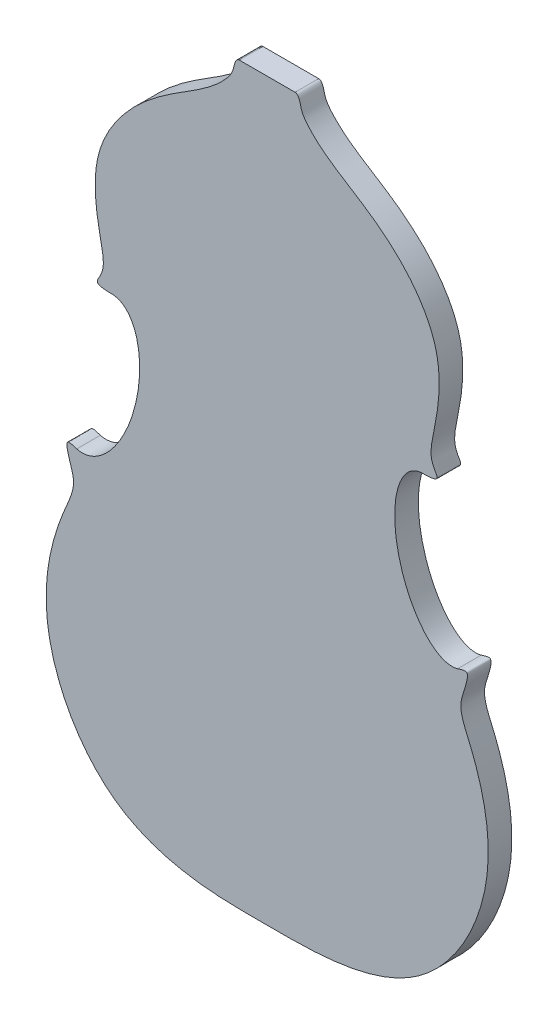
SolidWorks part; units mm, degrees
ref_plane "Front Plane" through (0, 0, 0) normal (0, 0, 1) x (1, 0, 0)
ref_plane "Top Plane" through (0, 0, 0) normal (0, 1, 0) x (1, 0, 0)
ref_plane "Right Plane" through (0, 0, 0) normal (1, 0, 0) x (0, 0, -1)
sketch "SketchPictureFront" plane through (0, 0, 0) normal (0, 0, 1) x (1, 0, 0)
  line L0 (-151.7172, 1634.9996) -> (638.2828, 1634.9996) construction
sketch "SketchPictureRight" plane through (0, 0, 0) normal (1, 0, 0) x (0, 0, -1)
  line L0 (-135.6802, 1539.0324) -> (654.3198, 1539.0324) construction
sketch "Sketch5" plane through (0, 0, 0) normal (0, 0, 1) x (1, 0, 0)
  line L0 (0, -554.9675) -> (0, 489.2296)
  line L1 (0, 489.2296) -> (39.526, 489.2296)
  line L2 (0, -554.9675) -> (-33.986, -554.9675) construction
  ellipse E0 centre (241.7303, 2.8151) end of major axis (269.6363, -104.5255) minor radius 55.6713 construction
  ellipse E1 centre (241.7303, 2.8151) end of major axis (269.6363, -104.5255) minor radius 55.6713 (270.371, -104.3238) -> (219.9912, 111.0476) cw
  spline S0 degree 3 poles (39.526, 489.2296) (41.9942, 489.2296) (46.5805, 483.709) (47.7623, 469.5398) (74.7703, 435.7587) (127.3468, 407.1292) (196.1476, 356.2641) (250.1218, 278.7198) (243.797, 200.2598) (231.4006, 148.6678) (233.2066, 129.4739) (246.1061, 111.4569) (223.5505, 111.0135) (219.9912, 111.0476) knots 0 0 0 0 0.004293 0.013713 0.029409 0.0918 0.139495 0.210643 0.278267 0.300685 0.318441 0.325162 0.331714 0.331714 0.331714 0.331714
  spline S1 degree 3 poles (270.371, -104.3238) (281.7873, -100.433) (286.6653, -102.9744) (280.0534, -125.9482) (270.8406, -151.6625) (307.7622, -226.6933) (330.7687, -359.3259) (234.5166, -526.5754) (103.9803, -554.0297) (29.3141, -555.0293) (6.9539, -554.9675) (0, -554.9675) knots 0.531516 0.531516 0.531516 0.531516 0.541192 0.55587 0.57021 0.600542 0.716993 0.8491 0.951451 0.984335 1 1 1 1
extrude "Boss-Extrude1" add sketch "Sketch5" against normal blind 33.528 contours S0 E1 S1 L0 L1
mirror "Mirror1" about plane through (0, -554.9675, -33.528) normal (1, 0, 0) of bodies 101
